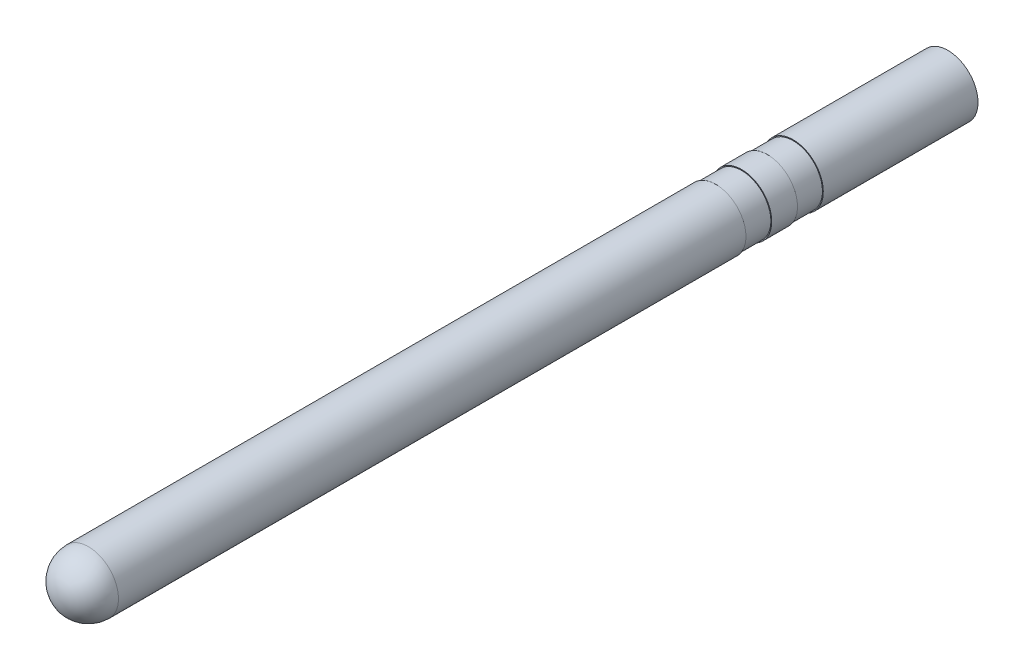
SolidWorks part; units mm, degrees
ref_plane "Front Plane" through (0, 0, 0) normal (0, 0, 1) x (1, 0, 0)
ref_plane "Top Plane" through (0, 0, 0) normal (0, 1, 0) x (1, 0, 0)
ref_plane "Right Plane" through (0, 0, 0) normal (1, 0, 0) x (0, 0, -1)
sketch "Sketch1" plane through (0, 0, 0) normal (1, 0, 0) x (0, 0, -1)
  line L0 (-135.5369, 0) -> (899.4631, 0)
  line L1 (-100.5369, -35) -> (629.4631, -35)
  line L2 (899.4631, -35) -> (719.4631, -35)
  line L3 (-100.5369, -35) -> (-100.5369, -38.7584)
  line L4 (629.4631, -34) -> (629.4631, -35)
  line L5 (719.4631, -35) -> (719.4631, -34)
  line L6 (719.4631, -34) -> (689.4631, -34)
  line L7 (689.4631, -34) -> (689.4631, -35)
  line L8 (689.4631, -35) -> (659.4631, -35)
  line L9 (659.4631, -35) -> (659.4631, -34)
  line L10 (659.4631, -34) -> (629.4631, -34)
  line L11 (899.4631, -35) -> (899.4631, 0)
  arc A0 (-135.5369, 0) -> (-100.5369, -35) centre (-100.5369, 0) ccw
  dimension "D1" = 70
  dimension "D2" = 730
  dimension "D3" = 1000
  dimension "D4" = 180
  dimension "D5" = 1
  dimension "D6" = 1
  dimension "D7" = 1
  dimension "D8" = 30
  dimension "D9" = 35
  dimension "D10" = 30
revolve "Revolve2" add sketch "Sketch1" angle 360 about L0
